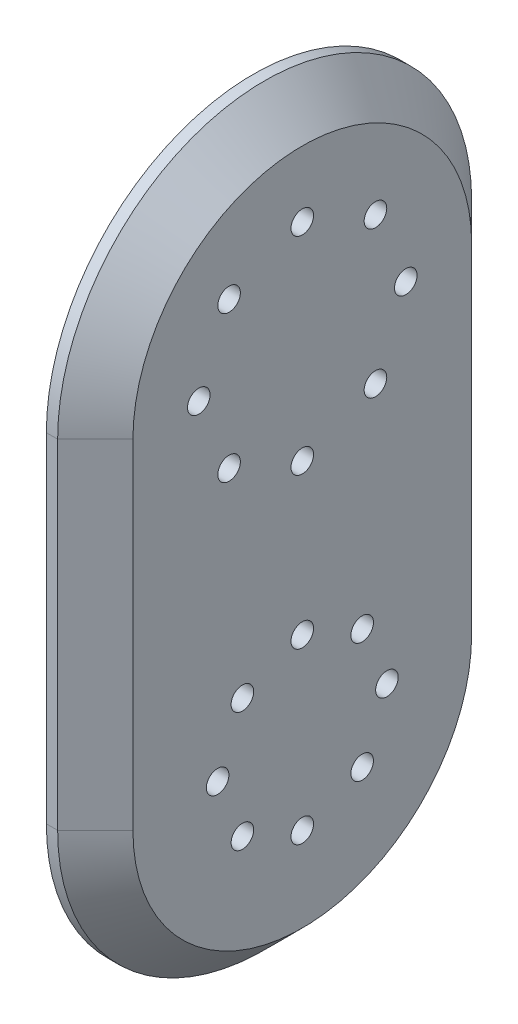
SolidWorks part; units mm, degrees
ref_plane "前视基准面" through (0, 0, 0) normal (0, 0, 1) x (1, 0, 0)
ref_plane "上视基准面" through (0, 0, 0) normal (0, 1, 0) x (1, 0, 0)
ref_plane "右视基准面" through (0, 0, 0) normal (1, 0, 0) x (0, 0, -1)
other "Configuration Table"
sketch "草图1" plane through (0, 0, 0) normal (1, 0, 0) x (0, 0, -1)
  line L0 (0, -45) -> (0, 45) construction
  line L1 (-55, -45) -> (-55, 45)
  line L2 (55, -45) -> (55, 45)
  arc A0 (-55, -45) -> (55, -45) centre (0, -45) ccw
  arc A1 (55, 45) -> (-55, 45) centre (0, 45) ccw
  point P2 (0, 0)
  dimension "D1" = 110
  dimension "D2" = 90
extrude "凸台-拉伸1" add sketch "草图1" along normal blind 13
chamfer "倒角1" distance 10 angle 45 4 edges at (13, 100, 0) (13, 0, 55) (13, 0, -55) (13, -100, 0)
sketch "草图2" plane through (0, 0, 0) normal (-1, 0, 0) x (0, 0, 1)
  circle A0 centre (0, 45) radius 23.5
  point P3 (0, 0)
  dimension "D1" = 47
extrude "切除-拉伸1" cut sketch "草图2" against normal blind 10
sketch "草图3" plane through (0, 0, 0) normal (-1, 0, 0) x (0, 0, 1)
  circle A0 centre (0, 72.5) radius 3
  circle A1 centre (0, 45) radius 23.5 construction
  circle A2 centre (19.4454, 64.4454) radius 3
  circle A3 centre (27.5, 45) radius 3
  circle A4 centre (19.4454, 25.5546) radius 3
  circle A5 centre (0, 17.5) radius 3
  circle A6 centre (-19.4454, 25.5546) radius 3
  circle A7 centre (-27.5, 45) radius 3
  circle A8 centre (-19.4454, 64.4454) radius 3
  point P4 (17.94, 61.4929)
  point P5 (0, 0)
  point P6 (0, 0)
  point P22 (0, 45)
  point P23 (0.3055, 44.8477)
  point P24 (-3.7802, 45.5063)
  dimension "D1" = 6
  dimension "D2" = 27.5
  dimension "D3" = 8
extrude "切除-拉伸2" cut sketch "草图3" against normal up to next
sketch "草图4" plane through (0, 0, 0) normal (-1, 0, 0) x (0, 0, 1)
  line L0 (-31, -45) -> (-31, -15)
  line L1 (-21, -5) -> (21, -5)
  line L2 (31, -15) -> (31, -45)
  arc A0 (-31, -45) -> (31, -45) centre (0, -45) ccw
  arc A1 (-55, -45) -> (55, -45) centre (0, -45) ccw construction
  arc A2 (21, -5) -> (31, -15) centre (21, -15) cw
  arc A3 (-31, -15) -> (-21, -5) centre (-21, -15) cw
  point P10 (31, -5)
  dimension "D1" = 62
  dimension "D3" = 10
  dimension "D2" = 40
extrude "切除-拉伸3" cut sketch "草图4" against normal blind 7
sketch "草图5" plane through (7, 0, 0) normal (-1, 0, 0) x (0, 0, 1)
  circle A0 centre (0, -45) radius 22.5 construction
  circle A1 centre (0, -22.5) radius 3
  circle A2 centre (15.9099, -29.0901) radius 3
  circle A3 centre (22.5, -45) radius 3
  circle A4 centre (15.9099, -60.9099) radius 3
  circle A5 centre (0, -67.5) radius 3
  circle A6 centre (-15.9099, -60.9099) radius 3
  circle A7 centre (-22.5, -45) radius 3
  circle A8 centre (-15.9099, -29.0901) radius 3
  point P5 (-14.5863, -35.6363)
  point P6 (0, 0)
  point P21 (0, -45)
  dimension "D1" = 45
  dimension "D2" = 6
  dimension "D3" = 8
extrude "切除-拉伸4" cut sketch "草图5" against normal blind 7
